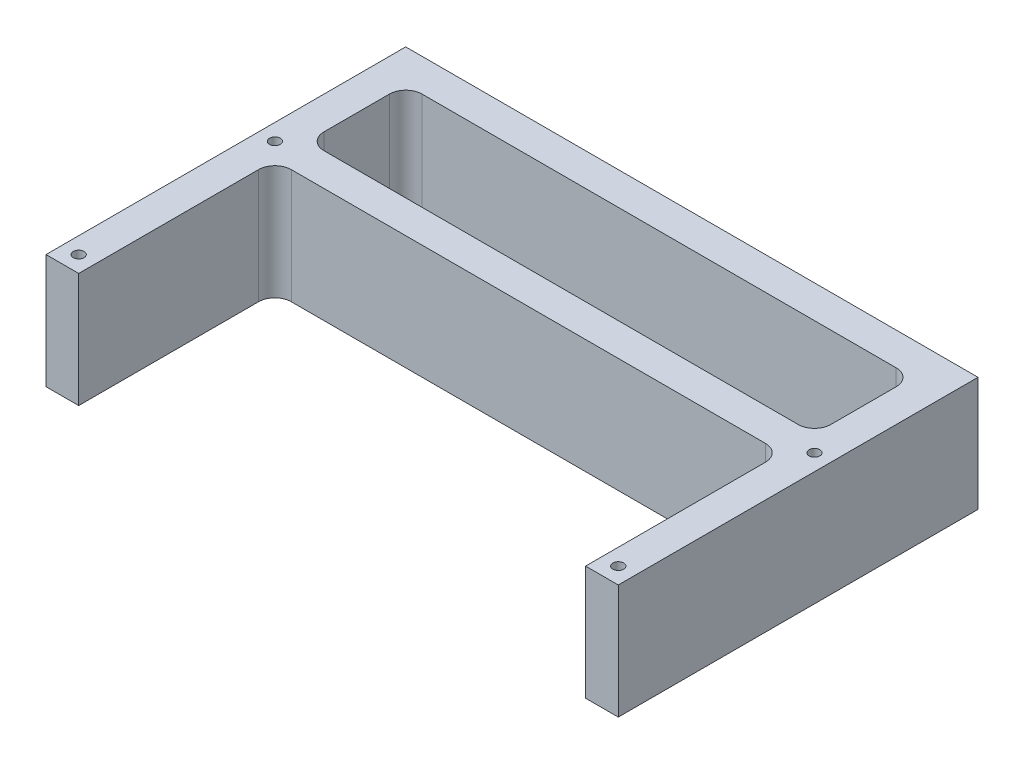
SolidWorks part; units mm, degrees
material "3D printed plastic"
ref_plane "Front Plane" through (0, 0, 0) normal (0, 0, 1) x (1, 0, 0)
ref_plane "Top Plane" through (0, 0, 0) normal (0, 1, 0) x (1, 0, 0)
ref_plane "Right Plane" through (0, 0, 0) normal (1, 0, 0) x (0, 0, -1)
sketch "Sketch1" plane through (0, 0, 0) normal (0, 1, 0) x (1, 0, 0)
  line L0 (-77.5, 15) -> (77.5, -15) construction
  line L1 (-77.5, 15) -> (77.5, 15)
  line L2 (-77.5, 15) -> (-77.5, -15)
  line L3 (-77.5, -15) -> (77.5, -15)
  line L4 (77.5, 15) -> (77.5, -15)
  line L5 (87.5, 25) -> (-87.5, -25) construction
  line L6 (-87.5, 25) -> (87.5, 25)
  line L7 (-87.5, 25) -> (-87.5, -25)
  line L8 (-77.5, -25) -> (77.5, -25)
  line L9 (87.5, 25) -> (87.5, -25)
  line L10 (-87.5, -85) -> (-77.5, -85)
  line L11 (77.5, -85) -> (87.5, -85)
  line L12 (-87.5, -25) -> (-87.5, -85)
  line L13 (0, 15) -> (0, 25) construction
  line L14 (-77.5, -25) -> (-77.5, -85)
  line L19 (87.5, -25) -> (87.5, -85)
  line L21 (77.5, -25) -> (77.5, -85)
  dimension "D1" = 155
  dimension "D2" = 30
  dimension "D3" = 10
  dimension "D4" = 10
  dimension "D6" = 60
extrude "Boss-Extrude1" add sketch "Sketch1" against normal mid plane 35
fillet "Fillet1" radius 5 6 edges at (77.5, 0, 15) (77.5, 0, 25) (77.5, 0, -15) (-77.5, 0, 15) (-77.5, 0, 25) (-77.5, 0, -15)
hole_wizard "M4 Tapped Hole2" positions "Sketch5" profile "Sketch4" tap size "M4" standard "DIN"
sketch "Sketch5" plane through (0, 17.5, 0) normal (0, 1, 0) x (1, 0, 0)
  line L0 (-82.5, -20) -> (-82.5, -80) construction
  line L1 (-82.5, -80) -> (82.5, -80) construction
  line L2 (82.5, -80) -> (82.5, -20) construction
  line L3 (82.5, -20) -> (-82.5, -20) construction
  line L5 (-82.5, -80) -> (-82.5, -85) construction
  line L6 (-87.5, -85) -> (-77.5, -85) construction
  line L9 (-82.5, -80) -> (-87.5, -80) construction
  line L10 (-87.5, 25) -> (-87.5, -85) construction
  line L12 (82.5, -80) -> (87.5, -80) construction
  line L13 (87.5, -85) -> (87.5, 25) construction
  line L15 (-82.5, -20) -> (-82.5, -15) construction
  line L17 (-72.5, -15) -> (72.5, -15) construction
  point P0 (-82.5, -20)
  point P2 (-82.5, -80)
  point P4 (82.5, -80)
  point P6 (82.5, -20)
sketch "Sketch4" plane through (-82.5, 17.5, 20) normal (1, 0, 0) x (0, 0, 1)
  line L0 (0, 0) -> (0, 16.9914)
  line L1 (0, 16.9914) -> (1.65, 16)
  line L2 (1.65, 16) -> (1.65, 0)
  line L5 (1.65, 0) -> (0, 0)
  line L10 (0, 16.9914) -> (-1.65, 16) construction
  line L11 (0, -6.35) -> (0, 107.95) construction
  dimension "Tap Drill Dia." = 3.3
  dimension "Tap Drill Depth" = 16
  dimension "Drill Angle" = 118
cosmetic thread "Hole Thread5" parameters "D1"=12, "D2"=4
cosmetic thread "Hole Thread6" parameters "D1"=12, "D2"=4
cosmetic thread "Hole Thread7" parameters "D1"=12, "D2"=4
cosmetic thread "Hole Thread8" parameters "D1"=12, "D2"=4
mirror "Mirror1" about plane through (0, 0, 0) normal (0, 1, 0) of "M4 Tapped Hole2"
